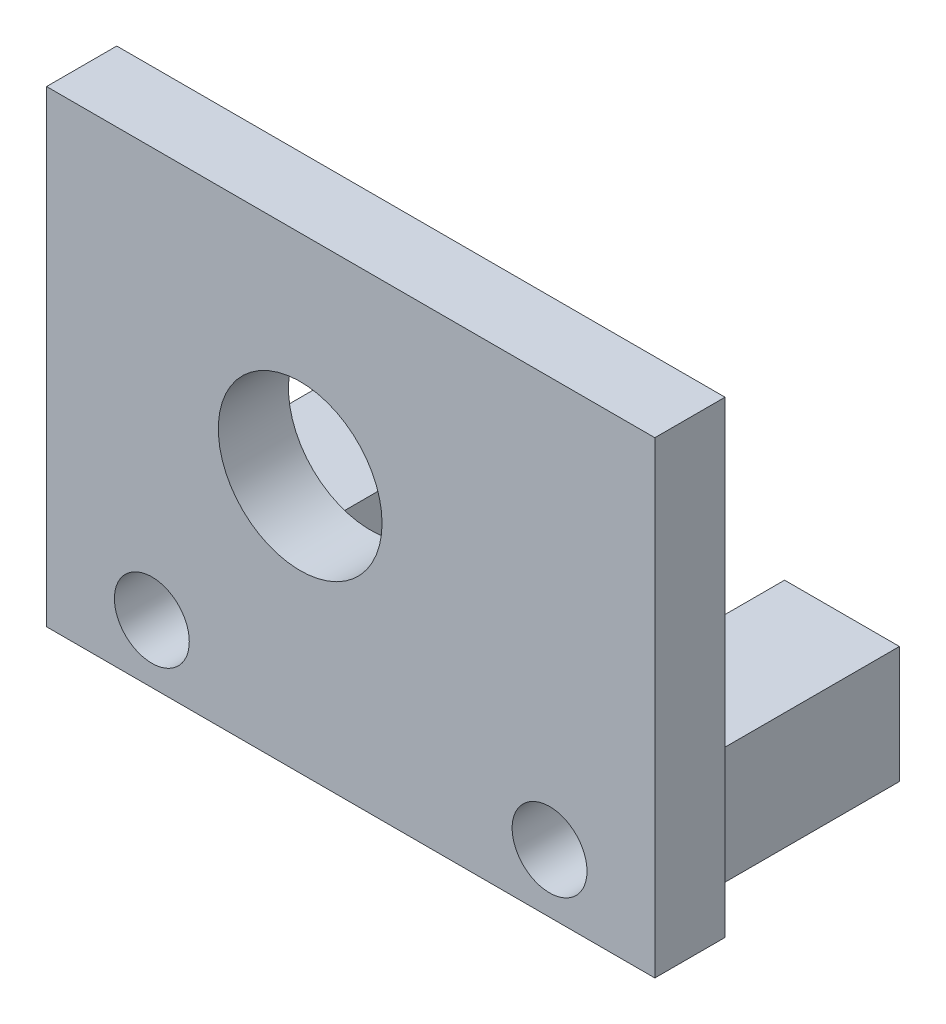
SolidWorks part; units mm, degrees
ref_plane "Front Plane" through (0, 0, 0) normal (0, 0, 1) x (1, 0, 0)
ref_plane "Top Plane" through (0, 0, 0) normal (0, 1, 0) x (1, 0, 0)
ref_plane "Right Plane" through (0, 0, 0) normal (1, 0, 0) x (0, 0, -1)
sketch "Sketch1" plane through (0, 0, 0) normal (0, 0, 1) x (1, 0, 0)
  line L0 (-6.34, -8.5) -> (10.66, -8.5) construction
  line L1 (-10.84, 9) -> (15.16, 9)
  line L2 (-10.84, 9) -> (-10.84, -11)
  line L3 (-10.84, -11) -> (15.16, -11)
  line L4 (15.16, 9) -> (15.16, -11)
  line L5 (2.16, -11) -> (2.16, 9) construction
  line L6 (-10.84, -1) -> (15.16, -1) construction
  line L7 (0, 0) -> (0, -8.5) construction
  circle A0 centre (0, 0) radius 3.5
  circle A1 centre (-6.34, -8.5) radius 1.6
  circle A2 centre (10.66, -8.5) radius 1.6
  point P12 (2.16, -8.5)
  point P415 (2.16, -1)
  dimension "D1" = 7
  dimension "D7" = 3.2
  dimension "D8" = 3.2
  dimension "D2" = 20
  dimension "D3" = 26
  dimension "D4" = 8.5
  dimension "D5" = 6.34
  dimension "D6" = 17
  dimension "D9" = 2.5
extrude "Boss-Extrude1" add sketch "Sketch1" along normal blind 3
sketch "Sketch2" plane through (0, 0, 0) normal (0, 0, 1) x (1, 0, 0)
  line L0 (-10.84, -11) -> (15.16, -11) construction
  line L1 (-8.9047, -6) -> (-3.7753, -6)
  line L2 (-8.9047, -6) -> (-8.9047, -11)
  line L3 (-8.9047, -11) -> (-3.7753, -11)
  line L4 (-3.7753, -6) -> (-3.7753, -11)
  line L5 (-6.34, -11) -> (-6.34, -6) construction
  line L6 (-8.9047, -8.5) -> (-3.7753, -8.5) construction
  line L8 (8.2054, -6) -> (13.1146, -6)
  line L9 (8.2054, -6) -> (8.2054, -11)
  line L10 (8.2054, -11) -> (13.1146, -11)
  line L11 (13.1146, -6) -> (13.1146, -11)
  line L12 (10.66, -11) -> (10.66, -6) construction
  line L13 (8.2054, -8.5) -> (13.1146, -8.5) construction
  circle A0 centre (-6.34, -8.5) radius 1.6
  circle A1 centre (10.66, -8.5) radius 1.6
extrude "Boss-Extrude2" add sketch "Sketch2" against normal blind 9.5
